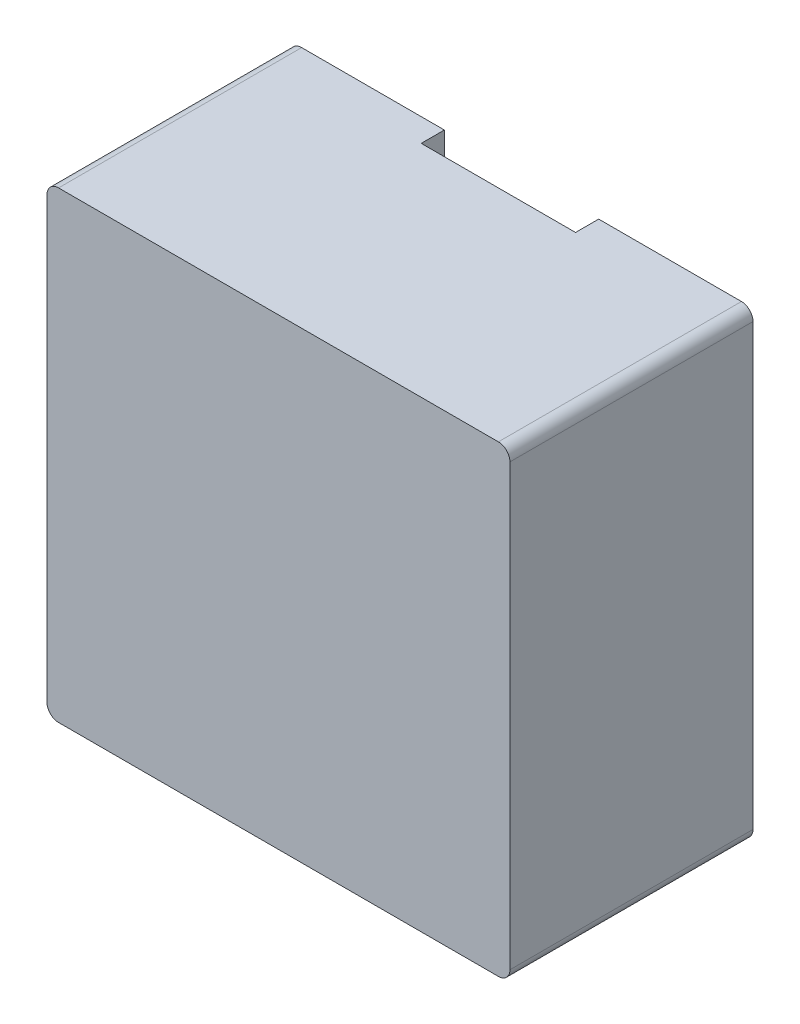
SolidWorks part; units mm, degrees
ref_plane "前视基准面" through (0, 0, 0) normal (0, 0, 1) x (1, 0, 0)
ref_plane "上视基准面" through (0, 0, 0) normal (0, 1, 0) x (1, 0, 0)
ref_plane "右视基准面" through (0, 0, 0) normal (1, 0, 0) x (0, 0, -1)
ref_plane "基准面1" through (0, 0, 0) normal (0, 0, -1) x (-1, 0, 0)
sketch "草图1" plane through (0, 0, 0) normal (0, 0, -1) x (-1, 0, 0)
  line L0 (-3, -3) -> (3, -3)
  line L1 (3, -3) -> (3, 3)
  line L2 (3, 3) -> (-3, 3)
  line L3 (-3, 3) -> (-3, -3)
extrude "凸台-拉伸1" add sketch "草图1" against normal blind 3.15
sketch "草图2" plane through (0, -3, 0) normal (0, -1, 0) x (1, 0, 0)
  line L0 (-1, 0) -> (1, 0)
  line L1 (1, 0) -> (1, 0.3)
  line L2 (1, 0.3) -> (-1, 0.3)
  line L3 (-1, 0.3) -> (-1, 0)
extrude "切除-拉伸1" cut sketch "草图2" against normal through all
fillet "圆角1" radius 0.15 4 edges at (-3, 3, 1.575) (-3, -3, 1.575) (3, 3, 1.575) (3, -3, 1.575)
